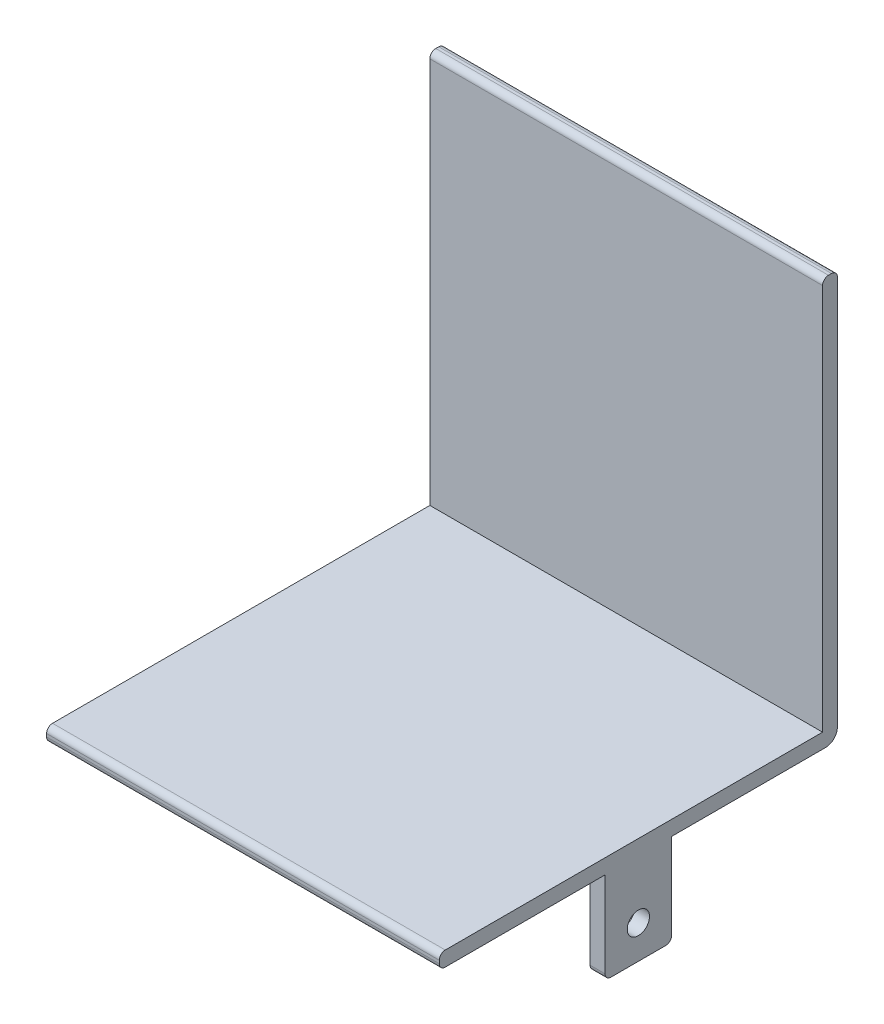
SolidWorks part; units mm, degrees
material "6061 Alloy"
ref_plane "Front Plane" through (0, 0, 0) normal (0, 0, 1) x (1, 0, 0)
ref_plane "Top Plane" through (0, 0, 0) normal (0, 1, 0) x (1, 0, 0)
ref_plane "Right Plane" through (0, 0, 0) normal (1, 0, 0) x (0, 0, -1)
sketch "Sketch11" plane through (0, 0, 0) normal (1, 0, 0) x (0, 0, -1)
  line L0 (0, 2.54) -> (0, 85.979)
  line L5 (-83.947, 0) -> (-2.54, 0)
  line L6 (-83.947, 3.175) -> (-3.175, 3.175)
  line L7 (-3.175, 3.175) -> (-3.175, 85.979)
  line L8 (-85.217, 1.905) -> (-85.217, 1.27)
  line L9 (-1.905, 87.249) -> (-1.27, 87.249)
  line L10 (-3.175, 3.175) -> (-3.175, 46.4733) construction
  line L11 (-48.2931, 0) -> (-2.54, 0) construction
  line L12 (-48.2931, 3.175) -> (-3.175, 3.175) construction
  line L13 (0, 2.54) -> (0, 46.4733) construction
  arc A0 (-2.54, 0) -> (0, 2.54) centre (-2.54, 2.54) ccw
  arc A1 (-3.175, 3.175) -> (-3.175, 3.175) centre (-3.175, 3.175) ccw
  arc A2 (-3.175, 85.979) -> (-1.905, 87.249) centre (-1.905, 85.979) cw
  arc A3 (-85.217, 1.27) -> (-83.947, 0) centre (-83.947, 1.27) ccw
  arc A4 (-83.947, 3.175) -> (-85.217, 1.905) centre (-83.947, 1.905) ccw
  arc A5 (0, 85.979) -> (-1.27, 87.249) centre (-1.27, 85.979) ccw
  point P5 (0, 0)
  dimension "D1" = 2.54
  dimension "D3" = 1.27
  dimension "D4" = 82.042
  dimension "D5" = 84.074
  dimension "D2" = 3.175
extrude "Boss-Extrude5" add sketch "Sketch11" along normal blind 84.074
sketch "Sketch12" plane through (84.074, 0, 0) normal (1, 0, 0) x (0, 0, -1)
  line L0 (-49.7522, -18.3281) -> (-49.7523, 0)
  line L1 (-49.7523, 0) -> (-35.4647, 0)
  line L2 (-35.4647, 0) -> (-35.4647, -18.3281)
  line L3 (-42.6085, 2.54) -> (-42.6085, -19.5981) construction
  line L4 (-48.4823, -19.5981) -> (-36.7347, -19.5981)
  line L6 (0, 2.54) -> (-85.217, 2.54) construction
  line L7 (-83.947, 0) -> (-2.54, 0) construction
  line L9 (-85.217, 1.905) -> (-85.217, 1.27) construction
  circle A0 centre (-42.6085, -12.4544) radius 2.3812
  arc A1 (-49.7522, -18.3281) -> (-48.4823, -19.5981) centre (-48.4823, -18.3281) ccw
  arc A2 (-35.4647, -18.3281) -> (-36.7347, -19.5981) centre (-36.7347, -18.3281) cw
  point P7 (-42.6085, 2.54)
  point P14 (-42.6085, -19.5981)
  point P17 (-49.7522, -19.5981)
  point P20 (-35.4647, -19.5981)
  point P21 (0, 0)
  point P22 (0, 0)
  point P23 (0, 2.54)
  dimension "D3" = 4.7625
  dimension "D4" = 1.27
  dimension "D1" = 14.2875
  dimension "D2" = 19.5981
  dimension "D5" = 7.1437
extrude "Boss-Extrude6" add sketch "Sketch12" against normal blind 3.175 from surface at 0 starting at face at (84.074, 32.5928, 31.8539)
